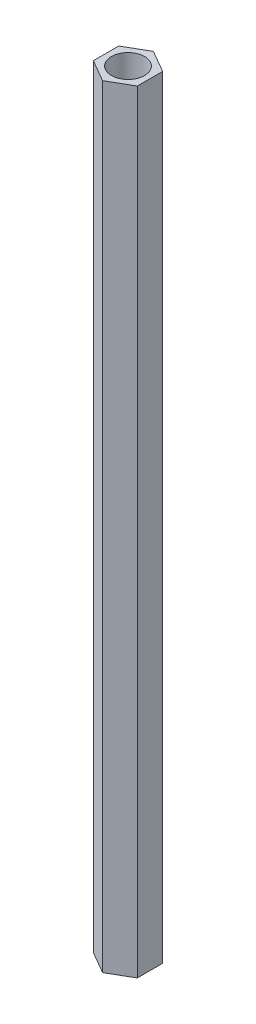
SolidWorks part; units mm, degrees
material "黄铜"
ref_plane "前视基准面" through (0, 0, 0) normal (0, 0, 1) x (1, 0, 0)
ref_plane "上视基准面" through (0, 0, 0) normal (0, 1, 0) x (1, 0, 0)
ref_plane "右视基准面" through (0, 0, 0) normal (1, 0, 0) x (0, 0, -1)
other "Configuration Table"
sketch "草图1" plane through (0, 0, 0) normal (0, 1, 0) x (1, 0, 0)
  line L0 (0, 0) -> (0, 2.2044) construction
  line L1 (0, 2.3) -> (-1.9919, 1.15)
  line L2 (-1.9919, 1.15) -> (-1.9919, -1.15)
  line L3 (-1.9919, -1.15) -> (0, -2.3)
  line L4 (0, -2.3) -> (1.9919, -1.15)
  line L5 (1.9919, -1.15) -> (1.9919, 1.15)
  line L6 (1.9919, 1.15) -> (0, 2.3)
  circle A0 centre (0, 0) radius 1.5
  circle A1 centre (0, 0) radius 1.9919 construction
  dimension "D1" = 3
  dimension "D2" = 4.6
extrude "凸台-拉伸1" add sketch "草图1" along normal blind 70
